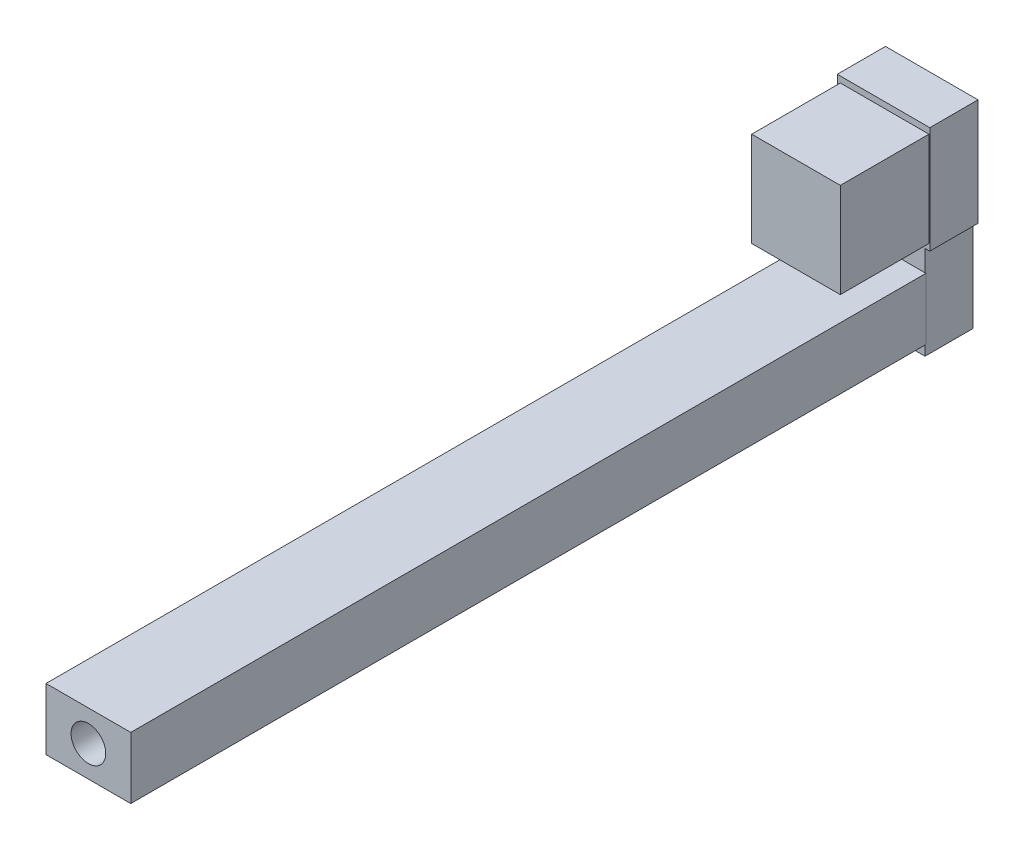
SolidWorks part; units mm, degrees
ref_plane "Front Plane" through (0, 0, 0) normal (0, 0, 1) x (1, 0, 0)
ref_plane "Top Plane" through (0, 0, 0) normal (0, 1, 0) x (1, 0, 0)
ref_plane "Right Plane" through (0, 0, 0) normal (1, 0, 0) x (0, 0, -1)
sketch "Sketch1" plane through (0, 0, 0) normal (1, 0, 0) x (0, 0, -1)
  line L1 (0, 50.8) -> (-1310.386, 50.8)
  line L2 (0, 50.8) -> (0, -50.8)
  line L3 (0, -50.8) -> (-1310.386, -50.8)
  line L4 (-1310.386, 50.8) -> (-1310.386, -50.8)
  point P4 (0, 0)
  dimension "D1" = 1310.386
  dimension "D2" = 101.6
  dimension "D3" = 0
extrude "Boss-Extrude1" add sketch "Sketch1" along normal mid plane 139.7
sketch "Sketch2" plane through (0, 0, 0) normal (1, 0, 0) x (0, 0, -1)
  line L0 (0, 0) -> (0, -68.326)
  line L1 (0, -68.326) -> (79.4308, -68.326)
  line L2 (79.4308, -68.326) -> (79.4308, 85.598)
  line L3 (79.4308, 85.598) -> (0, 85.598)
  line L4 (0, 85.598) -> (0, 0)
  dimension "D1" = 68.326
  dimension "D2" = 153.924
extrude "Boss-Extrude2" add sketch "Sketch2" along normal mid plane 136.652 contours L3 L4 L0 L1 L2
sketch "Sketch3" plane through (0, 0, 0) normal (1, 0, 0) x (0, 0, -1)
  line L1 (0, 85.598) -> (79.4308, 85.598)
  line L2 (0, 85.598) -> (0, 261.868)
  line L3 (0, 261.868) -> (79.4308, 261.868)
  line L4 (79.4308, 85.598) -> (79.4308, 261.868)
  dimension "D1" = 176.27
extrude "Boss-Extrude3" add sketch "Sketch3" along normal mid plane 152.46
sketch "Sketch4" plane through (0, 0, 0) normal (0, 0, 1) x (1, 0, 0)
  line L0 (-76.23, 261.868) -> (-76.23, 85.598) construction
  line L1 (-71.23, 251.868) -> (74.81, 251.868)
  line L2 (-71.23, 251.868) -> (-71.23, 95.828)
  line L3 (-71.23, 95.828) -> (74.81, 95.828)
  line L4 (74.81, 251.868) -> (74.81, 95.828)
  line L6 (76.23, 261.868) -> (-76.23, 261.868) construction
  dimension "D1" = 156.04
  dimension "D2" = 146.04
  dimension "D3" = 5
  dimension "D4" = 10
extrude "Boss-Extrude4" add sketch "Sketch4" along normal blind 146.05
sketch "Sketch5" plane through (0, 0, 1310.386) normal (0, 0, 1) x (1, 0, 0)
  circle A0 centre (0, 0) radius 28.575
  dimension "D1" = 57.15
extrude "Cut-Extrude1" cut sketch "Sketch5" against normal blind 927.1
